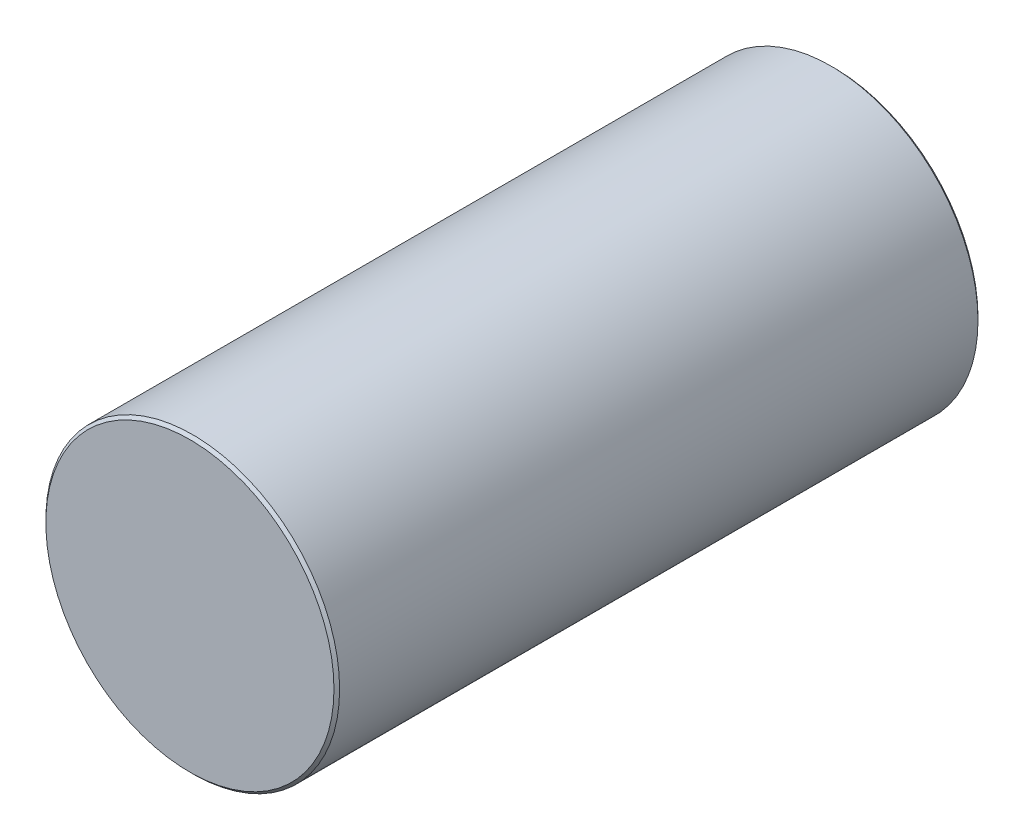
SolidWorks part; units mm, degrees
ref_plane "Front Plane" through (0, 0, 0) normal (0, 0, 1) x (1, 0, 0)
ref_plane "Top Plane" through (0, 0, 0) normal (0, 1, 0) x (1, 0, 0)
ref_plane "Right Plane" through (0, 0, 0) normal (1, 0, 0) x (0, 0, -1)
sketch "Sketch2" plane through (0, 0, 0) normal (0, 0, 1) x (1, 0, 0)
  circle A0 centre (0, 0) radius 2.6
  dimension "D1" = 5.2
extrude "Boss-Extrude1" add sketch "Sketch2" along normal blind 11.4
chamfer "Chamfer2" distance 0.05 angle 45 2 edges at (2.6, 0, 11.4) (2.6, 0, 0)
